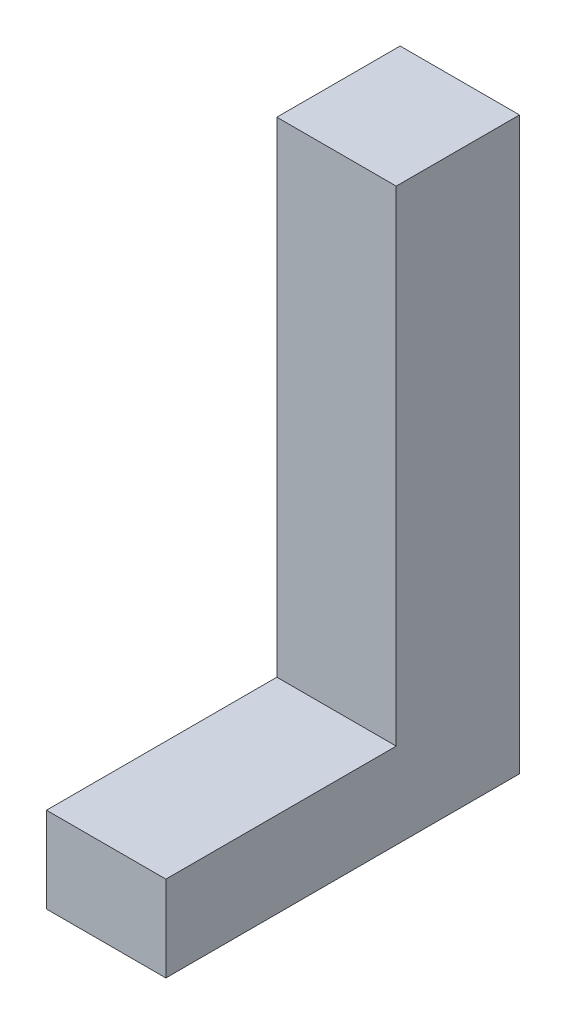
SolidWorks part; units mm, degrees
ref_plane "Front Plane" through (0, 0, 0) normal (0, 0, 1) x (1, 0, 0)
ref_plane "Top Plane" through (0, 0, 0) normal (0, 1, 0) x (1, 0, 0)
ref_plane "Right Plane" through (0, 0, 0) normal (1, 0, 0) x (0, 0, -1)
sketch "Sketch1" plane through (0, 0, -55.73) normal (0, 0, -1) x (-1, 0, 0)
  line L1 (160, 104) -> (305, 104)
  line L2 (160, 104) -> (160, 0)
  line L3 (160, 0) -> (305, 0)
  line L4 (305, 104) -> (305, 0)
extrude "Boss-Extrude1" add sketch "Sketch1" along normal blind 429.5145
sketch "Sketch2" plane through (0, 104, 0) normal (0, 1, 0) x (1, 0, 0)
  line L0 (-305, 485.2445) -> (-305, 55.73) construction
  line L1 (-160, 485.2445) -> (-305, 485.2445)
  line L2 (-160, 485.2445) -> (-160, 335.5069)
  line L3 (-160, 335.5069) -> (-305, 335.5069)
  line L4 (-305, 485.2445) -> (-305, 335.5069)
extrude "Boss-Extrude2" add sketch "Sketch2" along normal blind 589.0265
